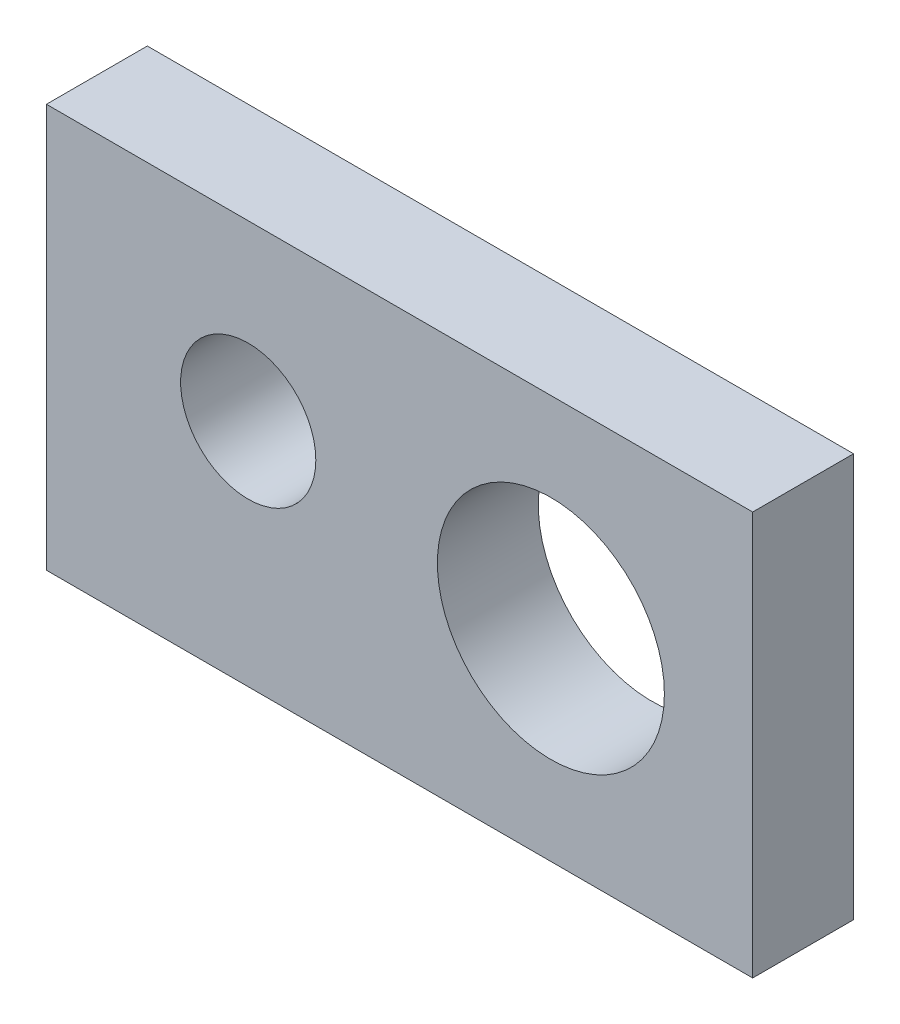
SolidWorks part; units mm, degrees
ref_plane "Front Plane" through (0, 0, 0) normal (0, 0, 1) x (1, 0, 0)
ref_plane "Top Plane" through (0, 0, 0) normal (0, 1, 0) x (1, 0, 0)
ref_plane "Right Plane" through (0, 0, 0) normal (1, 0, 0) x (0, 0, -1)
sketch "Sketch1" plane through (0, 0, 0) normal (0, 0, 1) x (1, 0, 0)
  line L1 (0, 0) -> (88.9, 0)
  line L2 (0, 0) -> (0, 50.8)
  line L3 (0, 50.8) -> (88.9, 50.8)
  line L4 (88.9, 0) -> (88.9, 50.8)
  dimension "D1" = 50.8
  dimension "D2" = 88.9
extrude "Boss-Extrude1" add sketch "Sketch1" along normal blind 12.7
sketch "Sketch2" plane through (0, 0, 12.7) normal (0, 0, 1) x (1, 0, 0)
  line L0 (0, 25.4) -> (88.9, 25.4) construction
  line L1 (0, 50.8) -> (0, 0) construction
  line L2 (88.9, 0) -> (88.9, 50.8) construction
  circle A0 centre (63.5, 25.4) radius 14.2875
  circle A1 centre (25.4, 28.956) radius 8.509
  dimension "D1" = 28.575
  dimension "D2" = 17.018
  dimension "D4" = 38.1
  dimension "D3" = 3.556
  dimension "D5" = 25.4
extrude "Cut-Extrude1" cut sketch "Sketch2" against normal through all
